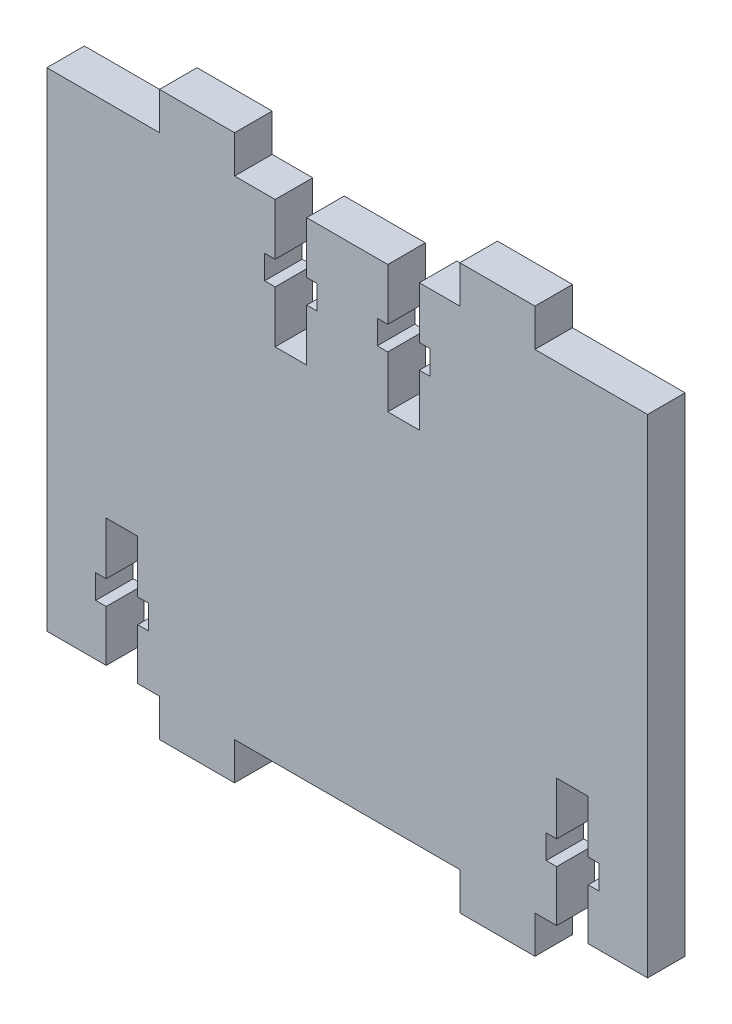
SolidWorks part; units mm, degrees
ref_plane "Front Plane" through (0, 0, 0) normal (0, 0, 1) x (1, 0, 0)
ref_plane "Top Plane" through (0, 0, 0) normal (0, 1, 0) x (1, 0, 0)
ref_plane "Right Plane" through (0, 0, 0) normal (1, 0, 0) x (0, 0, -1)
sketch "Sketch1" plane through (0, 0, 0) normal (0, 0, 1) x (1, 0, 0)
  line L0 (7.9656, 26.6306) -> (7.9656, 15.7877) construction
  line L1 (-32.0344, 26.6306) -> (47.9656, 26.6306)
  line L2 (-32.0344, 26.6306) -> (-32.0344, -38.3694)
  line L3 (-32.0344, -38.3694) -> (47.9656, -38.3694)
  line L4 (47.9656, 26.6306) -> (47.9656, -38.3694)
  line L5 (-17.0344, 26.6306) -> (32.9656, 26.6306)
  line L6 (-17.0344, 26.6306) -> (-17.0344, 31.6306)
  line L7 (-17.0344, 31.6306) -> (32.9656, 31.6306)
  line L8 (32.9656, 26.6306) -> (32.9656, 31.6306)
  line L9 (-17.0344, -38.3694) -> (32.9656, -38.3694)
  line L10 (-17.0344, -38.3694) -> (-17.0344, -43.3694)
  line L11 (-17.0344, -43.3694) -> (32.9656, -43.3694)
  line L12 (32.9656, -38.3694) -> (32.9656, -43.3694)
  line L29 (-32.0344, -5.8694) -> (-9.5344, -5.8694) construction
  line L30 (7.9656, -38.3694) -> (7.9656, -27.5265) construction
  line L31 (40.0656, -38.3694) -> (35.8656, -38.3694)
  line L32 (40.0656, -38.3694) -> (40.0656, -21.3694)
  line L33 (40.0656, -21.3694) -> (35.8656, -21.3694)
  line L34 (35.8656, -38.3694) -> (35.8656, -21.3694)
  line L35 (41.4656, -31.5694) -> (34.4656, -31.5694)
  line L36 (41.4656, -31.5694) -> (41.4656, -28.3694)
  line L37 (41.4656, -28.3694) -> (34.4656, -28.3694)
  line L38 (34.4656, -31.5694) -> (34.4656, -28.3694)
  line L39 (-18.5344, -31.5694) -> (-18.5344, -28.3694)
  line L40 (-25.5344, -28.3694) -> (-18.5344, -28.3694)
  line L41 (-25.5344, -31.5694) -> (-25.5344, -28.3694)
  line L42 (-25.5344, -31.5694) -> (-18.5344, -31.5694)
  line L43 (-19.9344, -38.3694) -> (-19.9344, -21.3694)
  line L44 (-24.1344, -21.3694) -> (-19.9344, -21.3694)
  line L45 (-24.1344, -38.3694) -> (-24.1344, -21.3694)
  line L46 (-24.1344, -38.3694) -> (-19.9344, -38.3694)
  line L47 (-7.0344, -38.3694) -> (22.9656, -38.3694)
  line L48 (-7.0344, 31.6306) -> (22.9656, 31.6306)
  line L49 (-7.0344, 31.6306) -> (-7.0344, 26.6306)
  line L50 (-7.0344, 26.6306) -> (22.9656, 26.6306)
  line L51 (22.9656, 31.6306) -> (22.9656, 26.6306)
  line L52 (22.9656, -43.3694) -> (22.9656, -38.3694)
  line L53 (-7.0344, -43.3694) -> (22.9656, -43.3694)
  line L54 (-7.0344, -43.3694) -> (-7.0344, -38.3694)
  line L55 (3.9656, 19.7306) -> (3.9656, 16.5436)
  line L56 (17.5656, 26.6306) -> (13.3656, 26.6306)
  line L57 (17.5656, 26.6306) -> (17.5656, 9.6306)
  line L58 (17.5656, 9.6306) -> (13.3656, 9.6306)
  line L59 (13.3656, 26.6306) -> (13.3656, 9.6306)
  line L60 (18.9656, 19.7306) -> (11.9656, 19.7306)
  line L61 (18.9656, 19.7306) -> (18.9656, 16.5436)
  line L62 (18.9656, 16.5436) -> (11.9656, 16.5436)
  line L63 (11.9656, 19.7306) -> (11.9656, 16.5436)
  line L64 (-3.0344, 16.5436) -> (3.9656, 16.5436)
  line L65 (-3.0344, 19.7306) -> (-3.0344, 16.5436)
  line L66 (-3.0344, 19.7306) -> (3.9656, 19.7306)
  line L67 (2.5656, 26.6306) -> (2.5656, 9.6306)
  line L68 (-1.6344, 9.6306) -> (2.5656, 9.6306)
  line L69 (-1.6344, 26.6306) -> (-1.6344, 9.6306)
  line L70 (-1.6344, 26.6306) -> (2.5656, 26.6306)
  point P12 (7.9656, -43.3694)
  point P13 (7.9656, 31.6306)
  point P14 (15.4656, 16.5436)
  point P15 (15.4656, 9.6306)
  dimension "D1" = 65
  dimension "D2" = 80
  dimension "D3" = 5
  dimension "D4" = 5
  dimension "D5" = 50
  dimension "D6" = 50
  dimension "D7" = 40
  dimension "D8" = 17
  dimension "D9" = 4.2
  dimension "D10" = 7
  dimension "D11" = 6.9
  dimension "D12" = 7.5
  dimension "D14" = 30
  dimension "D15" = 10
extrude "Boss-Extrude1" add sketch "Sketch1" along normal blind 5
